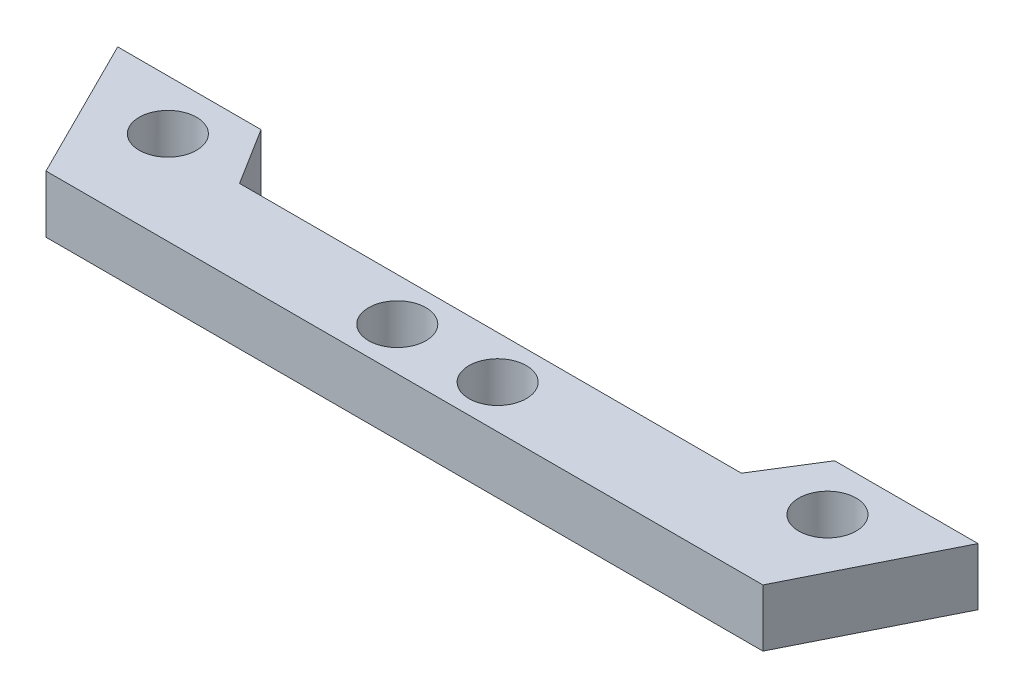
SolidWorks part; units mm, degrees
ref_plane "Front Plane" through (0, 0, 0) normal (0, 0, 1) x (1, 0, 0)
ref_plane "Top Plane" through (0, 0, 0) normal (0, 1, 0) x (1, 0, 0)
ref_plane "Right Plane" through (0, 0, 0) normal (1, 0, 0) x (0, 0, -1)
sketch "Sketch2" plane through (0, 0, 0) normal (0, 1, 0) x (1, 0, 0)
  line L1 (0, 0) -> (120, 0)
  line L2 (0, 0) -> (0, 20)
  line L3 (0, 20) -> (120, 20)
  line L4 (120, 0) -> (120, 20)
  dimension "D1" = 120
  dimension "D2" = 20
extrude "Boss-Extrude1" add sketch "Sketch2" along normal blind 8
sketch "Sketch3" plane through (0, 8, 0) normal (0, 1, 0) x (1, 0, 0)
  line L0 (0, 0) -> (120, 0) construction
  line L1 (120, 20) -> (0, 20) construction
  line L2 (60, 20) -> (60, 0)
  line L3 (10, 0) -> (0, 20)
  line L4 (0, 20) -> (20, 20)
  line L5 (20, 20) -> (25, 12)
  line L6 (110, 0) -> (120, 20)
  line L7 (120, 20) -> (100, 20)
  line L8 (100, 20) -> (95, 12)
  line L9 (25, 12) -> (95, 12)
  line L10 (0, 20) -> (0, 0) construction
  line L11 (0, 0) -> (10, 0) construction
  line L12 (120, 0) -> (110, 0) construction
  line L13 (120, 20) -> (120, 0) construction
  line L14 (20, 20) -> (100, 20)
  line L15 (20, 20) -> (100, 20)
  line L16 (100, 20) -> (20, 20)
  point P0 (10, 0)
  point P1 (20, 20)
  point P8 (25, 12)
  point P21 (60, 12)
  line M7 (0, 20) -> (0, 0)
  line M8 (0, 0) -> (120, 0)
  line M9 (120, 0) -> (120, 20)
  line M10 (120, 20) -> (0, 20)
extrude "Cut-Extrude1" cut sketch "Sketch3" against normal blind 40 contours L3 M8 M7 | L6 M8 M9 | L5 L9 L2 M10 | L2 L9 L8 M10
sketch "Sketch4" plane through (0, 8, 0) normal (0, 1, 0) x (1, 0, 0)
  line L0 (60, 0) -> (60, 25.0651) construction
  line L1 (10, 0) -> (110, 0) construction
  line L2 (53, 6) -> (53, 12) construction
  line L3 (53, 6) -> (53, 0) construction
  line L4 (25, 12) -> (95, 12) construction
  line L5 (25, 12) -> (95, 12)
  line L6 (10, 0) -> (110, 0)
  line L7 (20, 20) -> (0, 20) construction
  circle A0 centre (53, 6) radius 4
  circle A1 centre (14, 13) radius 4
  circle A2 centre (67, 6) radius 4
  circle A3 centre (106, 13) radius 4
  dimension "D1" = 8
  dimension "D3" = 8
  dimension "D2" = 7
  dimension "D4" = 7
  dimension "D5" = 46
extrude "Cut-Extrude2" cut sketch "Sketch4" against normal blind 10 contours A1 | A0 | A2 | A3
